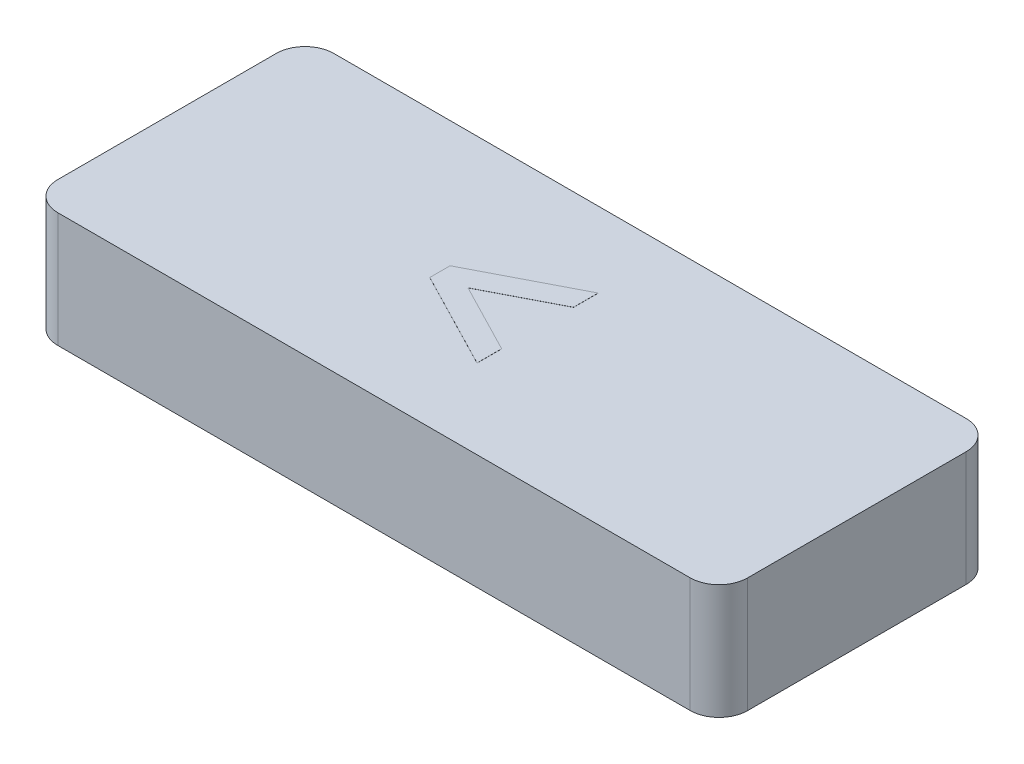
SolidWorks part; units mm, degrees
ref_plane "Front Plane" through (0, 0, 0) normal (0, 0, 1) x (1, 0, 0)
ref_plane "Top Plane" through (0, 0, 0) normal (0, 1, 0) x (1, 0, 0)
ref_plane "Right Plane" through (0, 0, 0) normal (1, 0, 0) x (0, 0, -1)
sketch "Sketch1" plane through (0, 0, 0) normal (0, 1, 0) x (1, 0, 0)
  line L0 (0, 0) -> (0, 6.096)
  line L1 (0, -54.9123) -> (0, 54.9123) construction
  line L2 (0, 6.096) -> (15.24, 6.096)
  line L3 (15.24, 6.096) -> (15.24, 0)
  line L4 (-55, 0) -> (55, 0) construction
  line L5 (15.24, 0) -> (0, 0)
  dimension "D1" = 15.24
  dimension "D2" = 6.096
extrude "Boss-Extrude1" add sketch "Sketch1" along normal blind 2.54 contours L2 L3 L5 L0
shell "Shell1" thickness 0.635
fillet "Fillet1" radius 0.635 4 edges at (15.24, 1.27, -6.096) (15.24, 1.27, 0) (0, 1.27, -6.096) (0, 1.27, 0)
sketch "Sketch2" plane through (0, 1.905, 0) normal (0, -1, 0) x (1, 0, 0)
  line L0 (14.605, -0.635) -> (0.635, -0.635) construction
  line L2 (7.62, -0.635) -> (7.62, -5.461) construction
  line L3 (0.635, -5.461) -> (14.605, -5.461) construction
  line L4 (0.635, -3.048) -> (14.605, -3.048) construction
  line L5 (0.635, -0.635) -> (0.635, -5.461) construction
  line L6 (14.605, -5.461) -> (14.605, -0.635) construction
  circle A0 centre (7.62, -3.048) radius 1.5875
  dimension "D1" = 3.175
extrude "Boss-Extrude2" add sketch "Sketch2" along normal up to surface (1.905 mm away) up to face at (7.62, 0, -3.048)
sketch "Sketch3" plane through (0, 2.54, 0) normal (0, 1, 0) x (1, 0, 0)
  line L0 (14.605, 0) -> (0.635, 0) construction
  line L1 (0, 0.635) -> (0, 5.461) construction
  text T0 "<b><</b>"
  point P3 (0, 0)
  dimension "D1" = 1.524
  dimension "D2" = 5.7404
extrude "Boss-Extrude3" add sketch "Sketch3" along normal blind 0.0025
